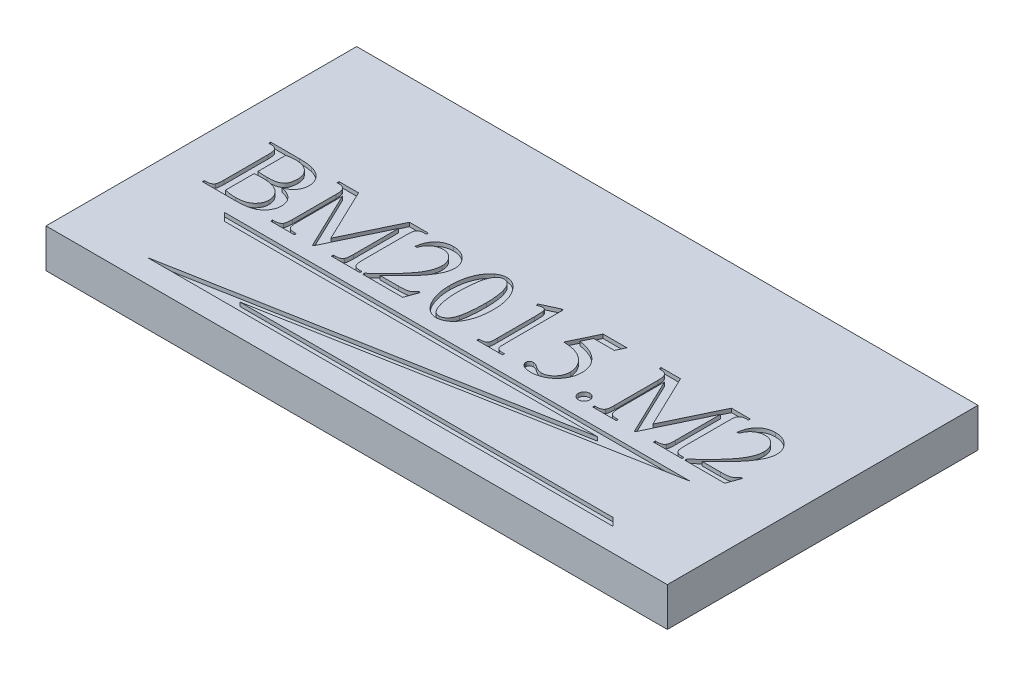
SolidWorks part; units mm, degrees
material "Д16Т ГОСТ 4784-74"
ref_plane "Спереди" through (0, 0, 0) normal (0, 0, 1) x (1, 0, 0)
ref_plane "Сверху" through (0, 0, 0) normal (0, 1, 0) x (1, 0, 0)
ref_plane "Сбоку" through (0, 0, 0) normal (1, 0, 0) x (0, 0, -1)
sketch "Эскиз1" plane through (0, 0, 0) normal (0, 1, 0) x (1, 0, 0)
  line L1 (-80, -40) -> (80, -40)
  line L2 (-80, -40) -> (-80, 40)
  line L3 (-80, 40) -> (80, 40)
  line L4 (80, -40) -> (80, 40)
  line L5 (-80, -40) -> (80, 40) construction
  line L6 (-80, 40) -> (80, -40) construction
  point P0 (0, 0)
  dimension "D1" = 80
  dimension "D2" = 160
extrude "Бобышка-Вытянуть1" add sketch "Эскиз1" along normal blind 10
sketch "Эскиз2" plane through (0, 10, 0) normal (0, 1, 0) x (1, 0, 0)
  line L0 (80, 40) -> (-80, 40) construction
  line L1 (-80, 40) -> (-80, -40) construction
  text T0 "BM2015.M2" font "Times New Roman" height in points 72
  dimension "D1" = 50
  dimension "D2" = 10
extrude "Вырез-Вытянуть1" cut sketch "Эскиз2" against normal blind 1
sketch "Эскиз3" plane through (0, 10, 0) normal (0, 1, 0) x (1, 0, 0)
  line L0 (-58, -16) -> (38.0328, -16)
  line L1 (38.0328, -16) -> (-60, -34)
  line L2 (-60, -34) -> (60, -34)
  line L3 (60, -34) -> (58, -32)
  line L4 (58, -32) -> (-38.0328, -32)
  line L5 (-38.0328, -32) -> (60, -14)
  line L6 (60, -14) -> (-60, -14)
  line L7 (-60, -14) -> (-58, -16)
  line L8 (-80, 40) -> (-80, -40) construction
  line L10 (80, -40) -> (80, 40) construction
  line L11 (-80, -40) -> (80, -40) construction
  point P7 (64.6731, -19.081)
  point P9 (0, 0)
  point P12 (-60, -14.2142)
  point P13 (-62.6752, -14.1697)
  point P14 (-64.758, -14.334)
  point P15 (60, -34.2875)
  point P16 (61.1944, -34.1979)
  dimension "D1" = 45
  dimension "D2" = 2
  dimension "D3" = 2
  dimension "D4" = 2
  dimension "D5" = 120
  dimension "D6" = 20
  dimension "D7" = 45
  dimension "D8" = 20
  dimension "D9" = 20
  dimension "D10" = 20
  dimension "D11" = 6
extrude "Вырез-Вытянуть2" cut sketch "Эскиз3" against normal blind 1
